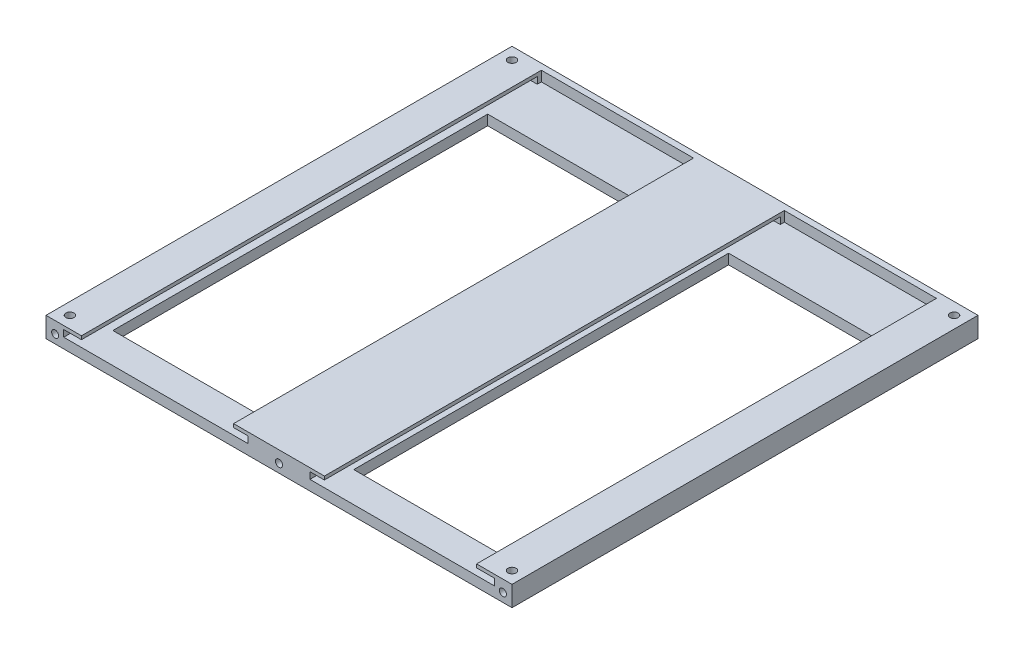
SolidWorks part; units mm, degrees
ref_plane "Alzado" through (0, 0, 0) normal (0, 0, 1) x (1, 0, 0)
ref_plane "Planta" through (0, 0, 0) normal (0, 1, 0) x (1, 0, 0)
ref_plane "Vista lateral" through (0, 0, 0) normal (1, 0, 0) x (0, 0, -1)
sketch "Croquis1" plane through (0, 0, 0) normal (0, 1, 0) x (1, 0, 0)
  line L1 (-115, 115) -> (115, 115)
  line L2 (-115, 115) -> (-115, -115)
  line L3 (-115, -115) -> (115, -115)
  line L4 (115, 115) -> (115, -115)
  line L5 (-115, 115) -> (115, -115) construction
  line L6 (-115, -115) -> (115, 115) construction
  circle A0 centre (109.1001, 109.1001) radius 2
  circle A1 centre (-109.1001, 109.1001) radius 2
  circle A2 centre (-109.1001, -109.1001) radius 2
  circle A3 centre (109.1001, -109.1001) radius 2
  point P0 (0, 0)
  dimension "D3" = 4
  dimension "D4" = 4
  dimension "D5" = 4
  dimension "D6" = 4
  dimension "D1" = 230
  dimension "D2" = 230
extrude "Saliente-Extruir1" add sketch "Croquis1" along normal blind 5
sketch "Croquis2" plane through (0, 5, 0) normal (0, 1, 0) x (1, 0, 0)
  line L0 (-115, -115) -> (115, -115) construction
  line L1 (-115, 115) -> (-97.5101, 115)
  line L2 (-115, 115) -> (-115, -115)
  line L3 (-115, -115) -> (-97.5101, -115)
  line L4 (-97.5101, 115) -> (-97.5101, -115)
  line L5 (0, 0) -> (0, -91.0198) construction
  line L6 (-22.4072, 115) -> (22.4072, 115)
  line L7 (-22.4072, 115) -> (-22.4072, -115)
  line L8 (-22.4072, -115) -> (22.4072, -115)
  line L9 (22.4072, 115) -> (22.4072, -115)
  line L10 (-22.4072, 115) -> (22.4072, -115) construction
  line L11 (-22.4072, -115) -> (22.4072, 115) construction
  line L12 (97.5101, 115) -> (97.5101, -115)
  line L13 (115, -115) -> (97.5101, -115)
  line L14 (115, 115) -> (115, -115)
  line L15 (115, 115) -> (97.5101, 115)
  point P7 (0, 0)
extrude "Saliente-Extruir2" add sketch "Croquis2" along normal blind 5
sketch "Croquis3" plane through (0, 0, 115) normal (0, 0, 1) x (1, 0, 0)
  line L0 (106.2551, 10) -> (106.2551, 5) construction
  line L1 (-106.2551, 8.3) -> (-15.2551, 8.3)
  line L2 (-106.2551, 8.3) -> (-106.2551, 5)
  line L3 (-106.2551, 5) -> (-15.2551, 5)
  line L4 (-15.2551, 8.3) -> (-15.2551, 5)
  line L5 (-106.2551, 10) -> (-106.2551, 5) construction
  line L6 (-115, 10) -> (-97.5101, 10) construction
  line L7 (0, 0) -> (0, -30.0029) construction
  line L8 (15.2551, 8.3) -> (15.2551, 5)
  line L9 (106.2551, 5) -> (15.2551, 5)
  line L10 (106.2551, 8.3) -> (106.2551, 5)
  line L11 (106.2551, 8.3) -> (15.2551, 8.3)
  line L13 (-115, 0) -> (115, 0) construction
  dimension "D1" = 3.3
  dimension "D3" = 5
extrude "Cortar-Extruir1" cut sketch "Croquis3" against normal blind 225
sketch "Croquis4" plane through (0, 5, 0) normal (0, 1, 0) x (1, 0, 0)
  line L0 (-115, 115) -> (-115, -115) construction
  line L1 (-97, 85) -> (-21.8971, 85)
  line L2 (-97, 85) -> (-97, -100)
  line L3 (-97, -100) -> (-21.8971, -100)
  line L4 (-21.8971, 85) -> (-21.8971, -100)
  line L5 (-115, -115) -> (115, -115) construction
  line L6 (0, 0) -> (0, -59.8042) construction
  line L7 (21.8971, 85) -> (21.8971, -100)
  line L8 (97, -100) -> (21.8971, -100)
  line L9 (97, 85) -> (97, -100)
  line L10 (97, 85) -> (21.8971, 85)
  dimension "D1" = 185
  dimension "D2" = 18
  dimension "D3" = 15
extrude "Cortar-Extruir2" cut sketch "Croquis4" against normal blind 256
sketch "Croquis5" plane through (0, 0, 0) normal (0, -1, 0) x (1, 0, 0)
  circle A1 centre (-82, 105) radius 2.6
  circle A3 centre (-36, 105) radius 2.6
  circle A4 centre (-13, 105) radius 2.6
  circle A5 centre (10, 105) radius 2.6
  circle A6 centre (33, 105) radius 2.6
  circle A8 centre (79, 105) radius 2.6
  circle A13 centre (-13, 82) radius 2.6
  circle A14 centre (10, 82) radius 2.6
  circle A18 centre (102, 82) radius 2.6
  circle A40 centre (-13, 13) radius 2.6
  circle A41 centre (10, 13) radius 2.6
  circle A45 centre (102, 13) radius 2.6
  circle A49 centre (-13, -10) radius 2.6
  circle A50 centre (10, -10) radius 2.6
  circle A54 centre (102, -10) radius 2.6
  circle A76 centre (-13, -79) radius 2.6
  circle A77 centre (10, -79) radius 2.6
  circle A81 centre (102, -79) radius 2.6
  circle A82 centre (-82, -102) radius 2.6
  circle A84 centre (-36, -102) radius 2.6
  circle A85 centre (-13, -102) radius 2.6
  circle A86 centre (10, -102) radius 2.6
  circle A87 centre (33, -102) radius 2.6
  circle A89 centre (79, -102) radius 2.6
  circle A91 centre (-105, 82) radius 2.6
  circle A94 centre (-105, 13) radius 2.6
  circle A95 centre (-105, -10) radius 2.6
  circle A98 centre (-105, -79) radius 2.6
extrude "Cortar-Extruir3" cut sketch "Croquis5" against normal blind 4
sketch "Croquis6" plane through (0, 0, 0) normal (0, -1, 0) x (1, 0, 0)
  line L0 (115, -115) -> (-115, -115) construction
  line L1 (-115, 115) -> (0, 115)
  line L2 (-115, 115) -> (-115, -115)
  line L3 (-115, -115) -> (0, -115)
  line L4 (0, 115) -> (0, -115)
  line L6 (-97, 100) -> (-21.8971, 100)
  line L7 (-97, 100) -> (-97, -85)
  line L8 (-97, -85) -> (-21.8971, -85)
  line L9 (-21.8971, 100) -> (-21.8971, -85)
sketch "Croquis13" plane through (0, 5, 0) normal (0, -1, 0) x (1, 0, 0)
  circle A0 centre (-109.1001, 109.1001) radius 2
  circle A1 centre (109.1001, 109.1001) radius 2
  circle A2 centre (109.1001, -109.1001) radius 2
  circle A3 centre (-109.1001, -109.1001) radius 2
extrude "Cortar-Extruir5" cut sketch "Croquis13" against normal blind 88
sketch "Croquis14" plane through (0, 0, 0) normal (0, -1, 0) x (-1, 0, 0)
  line L0 (0, 0) -> (58.2032, 0) construction
  line L1 (0, -115) -> (0, 115) construction
  line L2 (58.2032, 0) -> (0, 0) construction
  line L3 (0, 0) -> (0, -31.9449) construction
  circle A0 centre (109.1001, -109.1001) radius 3
  circle A1 centre (-109.1001, -109.1001) radius 3
  circle A2 centre (-109.1001, 109.1001) radius 3
  circle A3 centre (109.1001, 109.1001) radius 3
  dimension "D1" = 6
extrude "Cortar-Extruir6" cut sketch "Croquis14" against normal blind 3
sketch "Croquis16" plane through (0, 0, 115) normal (0, 0, 1) x (1, 0, 0)
  line L0 (0, 0) -> (0, -17.6941) construction
  line L1 (-115, 0) -> (115, 0) construction
  circle A0 centre (0, 4.2793) radius 1.75
  circle A1 centre (110.4907, 4.2793) radius 1.75
  circle A2 centre (-110.4907, 4.2793) radius 1.75
  dimension "D1" = 3.5
  dimension "D2" = 3.5
extrude "Cortar-Extruir7" cut sketch "Croquis16" against normal blind 3
sketch "Croquis17" plane through (0, 0, 115) normal (0, 0, 1) x (1, 0, 0)
  line L1 (115, 0) -> (-115, 0)
  line L2 (115, 0) -> (115, 10)
  line L3 (115, 10) -> (-115, 10)
  line L4 (-115, 0) -> (-115, 10)
  circle A0 centre (0, 4.2793) radius 1.75
  circle A1 centre (-110.4907, 4.2793) radius 1.7688
  circle A2 centre (110.4907, 4.2793) radius 1.75
sketch "Croquis18" plane through (0, 0, -115) normal (0, 0, -1) x (-1, 0, 0)
  line L1 (-115, 10) -> (115, 10)
  line L2 (-115, 10) -> (-115, 0)
  line L3 (-115, 0) -> (115, 0)
  line L4 (115, 10) -> (115, 0)
extrude "Saliente-Extruir4" add sketch "Croquis18" against normal blind 3
